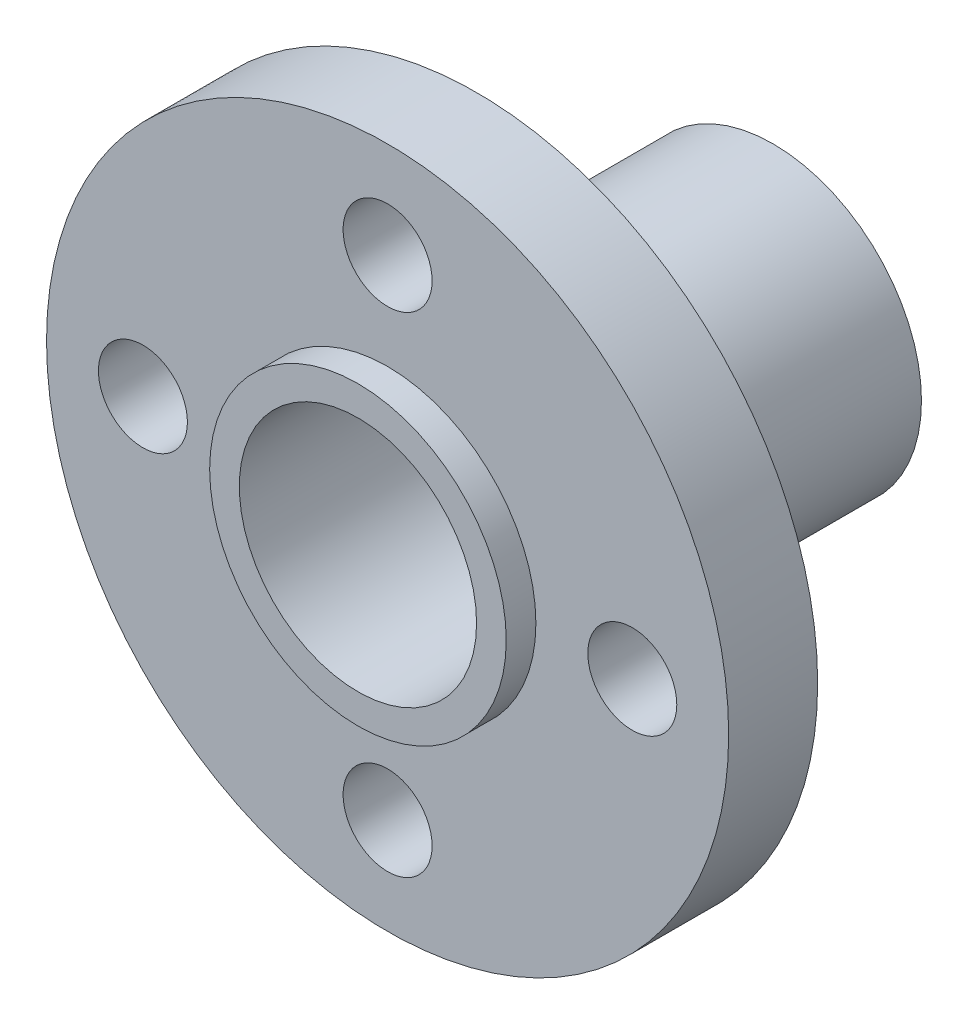
SolidWorks part; units mm, degrees
ref_plane "Front Plane" through (0, 0, 0) normal (0, 0, 1) x (1, 0, 0)
ref_plane "Top Plane" through (0, 0, 0) normal (0, 1, 0) x (1, 0, 0)
ref_plane "Right Plane" through (0, 0, 0) normal (1, 0, 0) x (0, 0, -1)
sketch "Sketch1" plane through (0, 0, 0) normal (0, 0, 1) x (1, 0, 0)
  circle A0 centre (0, 0) radius 11.5
  dimension "D1" = 23
extrude "Boss-Extrude1" add sketch "Sketch1" along normal blind 3
sketch "Sketch2" plane through (0, 0, 3) normal (0, 0, 1) x (1, 0, 0)
  circle A0 centre (0, 0) radius 4
  circle A1 centre (0, 0) radius 5
  dimension "D1" = 8
  dimension "D2" = 1
extrude "Boss-Extrude2" add sketch "Sketch2" along normal blind 1 and the other way blind 13
sketch "Sketch3" plane through (0, 0, 3) normal (0, 0, 1) x (1, 0, 0)
  circle A0 centre (0, 0) radius 4
extrude "Cut-Extrude1" cut sketch "Sketch3" against normal blind 5
sketch "Sketch4" plane through (0, 0, 3) normal (0, 0, 1) x (1, 0, 0)
  line L0 (0, 5) -> (0, 11.5) construction
  line L1 (11.5, 0) -> (5, 0) construction
  line L2 (0, -5) -> (0, -11.5) construction
  line L3 (-5, 0) -> (-11.5, 0) construction
  circle A1 centre (0, 0) radius 5 construction
  circle A2 centre (0, 0) radius 5 construction
  circle A3 centre (0, 0) radius 11.5 construction
  circle A4 centre (0, 8.25) radius 1.5
  circle A5 centre (8.25, 0) radius 1.5
  circle A6 centre (0, -8.25) radius 1.5
  circle A7 centre (-8.25, 0) radius 1.5
  dimension "D1" = 3
  dimension "D2" = 3
  dimension "D3" = 3
  dimension "D4" = 3
extrude "Cut-Extrude2" cut sketch "Sketch4" against normal blind 5
